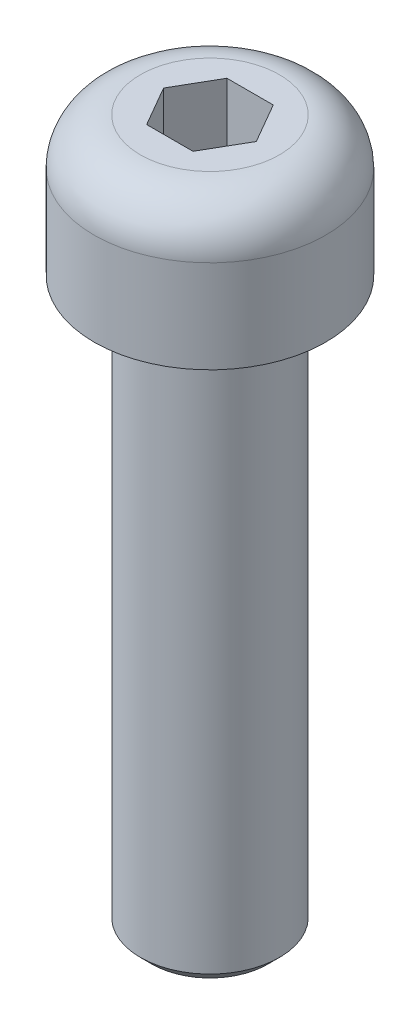
SolidWorks part; units mm, degrees
material "Cast Carbon Steel"
ref_plane "Front Plane" through (0, 0, 0) normal (0, 0, 1) x (1, 0, 0)
ref_plane "Top Plane" through (0, 0, 0) normal (0, 1, 0) x (1, 0, 0)
ref_plane "Right Plane" through (0, 0, 0) normal (1, 0, 0) x (0, 0, -1)
sketch "Sketch1" plane through (0, 0, 0) normal (0, 1, 0) x (1, 0, 0)
  circle A0 centre (0, 0) radius 1.5
  dimension "D1" = 3
extrude "Boss-Extrude1" add sketch "Sketch1" along normal blind 12.25
sketch "Sketch2" plane through (0, 12.25, 0) normal (0, 1, 0) x (1, 0, 0)
  circle A0 centre (0, 0) radius 2.5
  dimension "D1" = 5
extrude "Boss-Extrude2" add sketch "Sketch2" along normal blind 3
fillet "Fillet1" radius 1 1 edges at (0, 15.25, 2.5)
chamfer "Chamfer1" distance 0.25 angle 45 1 edges at (0, 0, 1.5)
sketch "Sketch3" plane through (0, 15.25, 0) normal (0, 1, 0) x (1, 0, 0)
  line L1 (-1, 0) -> (-0.5, -0.866)
  line L2 (-0.5, -0.866) -> (0.5, -0.866)
  line L3 (0.5, -0.866) -> (1, 0)
  line L4 (1, 0) -> (0.5, 0.866)
  line L5 (0.5, 0.866) -> (-0.5, 0.866)
  line L6 (-0.5, 0.866) -> (-1, 0)
  circle A0 centre (0, 0) radius 0.866 construction
  dimension "D1" = 1
extrude "Cut-Extrude1" cut sketch "Sketch3" against normal blind 2
